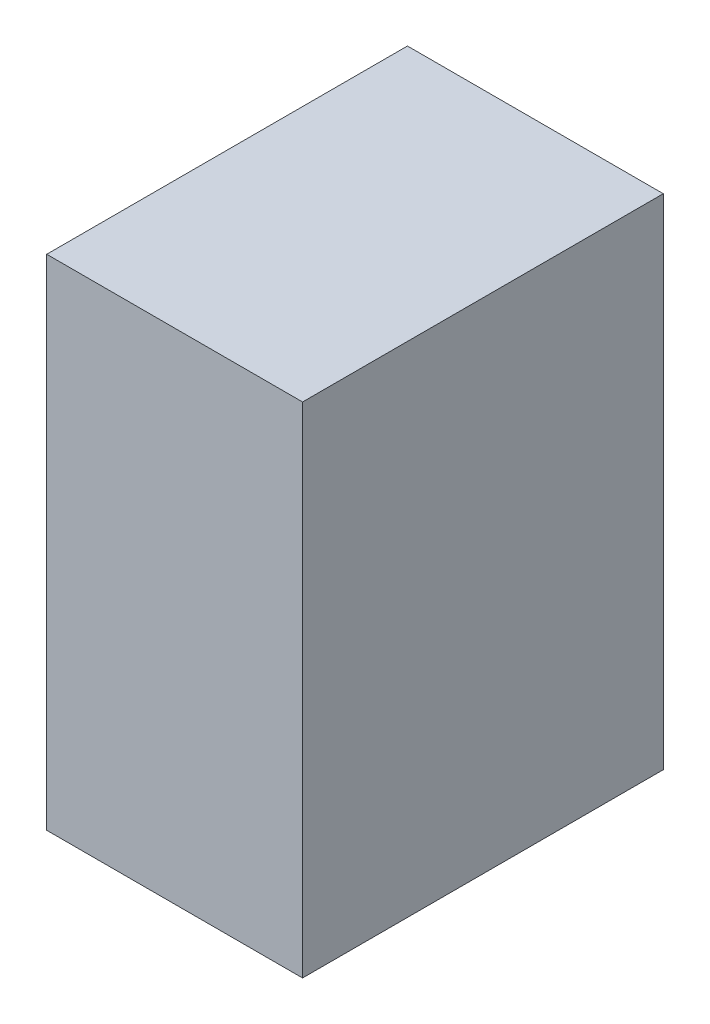
SolidWorks part; units mm, degrees
ref_plane "Front Plane" through (0, 0, 0) normal (0, 0, 1) x (1, 0, 0)
ref_plane "Top Plane" through (0, 0, 0) normal (0, 1, 0) x (1, 0, 0)
ref_plane "Right Plane" through (0, 0, 0) normal (1, 0, 0) x (0, 0, -1)
sketch "Sketch1" plane through (0, 0, 0) normal (1, 0, 0) x (0, 0, -1)
  line L1 (0, 0) -> (35.814, 0)
  line L2 (0, 0) -> (0, 49.53)
  line L3 (0, 49.53) -> (35.814, 49.53)
  line L4 (35.814, 0) -> (35.814, 49.53)
  dimension "D1" = 49.53
  dimension "D2" = 35.814
extrude "Boss-Extrude1" add sketch "Sketch1" along normal blind 25.4
